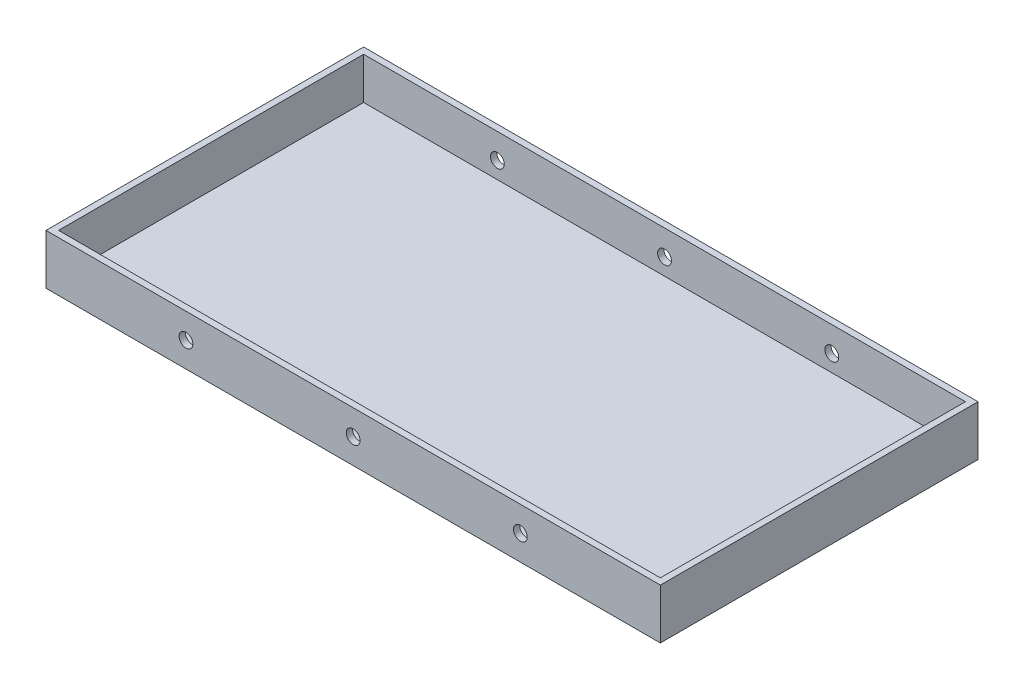
SolidWorks part; units mm, degrees
ref_plane "前视基准面" through (0, 0, 0) normal (0, 0, 1) x (1, 0, 0)
ref_plane "上视基准面" through (0, 0, 0) normal (0, 1, 0) x (1, 0, 0)
ref_plane "右视基准面" through (0, 0, 0) normal (1, 0, 0) x (0, 0, -1)
sketch "草图1" plane through (0, 0, 0) normal (0, 1, 0) x (1, 0, 0)
  line L0 (0, 38) -> (147, 38) construction
  line L1 (0, 0) -> (147, 0)
  line L2 (0, 0) -> (0, 76)
  line L3 (0, 76) -> (147, 76)
  line L4 (147, 0) -> (147, 76)
  line L5 (73.5, 76) -> (73.5, 0) construction
  line L7 (38, 45.75) -> (109, 45.75) construction
  line L8 (38, 45.75) -> (38, 30.25) construction
  line L9 (38, 30.25) -> (109, 30.25) construction
  line L10 (109, 45.75) -> (109, 30.25) construction
  line L11 (38, 45.75) -> (109, 30.25) construction
  line L12 (38, 30.25) -> (109, 45.75) construction
  circle A0 centre (111.25, 30) radius 1.2 construction
  circle A1 centre (111.25, 46) radius 1.2 construction
  circle A2 centre (35.75, 30) radius 1.2 construction
  circle A3 centre (35.75, 46) radius 1.2 construction
  point P9 (73.5, 38)
  dimension "D5" = 16
  dimension "D6" = 75.5
  dimension "D7" = 2.4
  dimension "D1" = 147
  dimension "D2" = 76
  dimension "D3" = 71
  dimension "D4" = 15.5
extrude "凸台-拉伸1" add sketch "草图1" along normal blind 12
sketch "草图2" plane through (0, 12, 0) normal (0, 1, 0) x (1, 0, 0)
  line L8 (1.5, 74.5) -> (1.5, 1.5)
  line L9 (1.5, 1.5) -> (145.5, 1.5)
  line L10 (145.5, 1.5) -> (145.5, 74.5)
  line L11 (145.5, 74.5) -> (1.5, 74.5)
  line L12 (1.5, 74.5) -> (1.5, 1.5)
  line L13 (1.5, 1.5) -> (145.5, 1.5)
  line L14 (145.5, 1.5) -> (145.5, 74.5)
  line L15 (145.5, 74.5) -> (1.5, 74.5)
  dimension "D1" = 1.5
extrude "切除-拉伸1" cut sketch "草图2" against normal offset from surface (10 mm away) 2 up to face at (73.5, 0, -38)
sketch "草图3" plane through (0, 0, -76) normal (0, 0, -1) x (-1, 0, 0)
  line L0 (-147, 6) -> (0, 6) construction
  line L1 (-147, 12) -> (-147, 0) construction
  line L2 (0, 12) -> (0, 0) construction
  line L3 (-73.5, 6) -> (-73.5, 17.272) construction
  circle A0 centre (-113.5, 6) radius 1.65
  circle A1 centre (-33.5, 6) radius 1.65
  circle A2 centre (-73.5, 6) radius 1.65
  dimension "D1" = 3.3
  dimension "D2" = 80
extrude "切除-拉伸2" cut sketch "草图3" against normal through all
